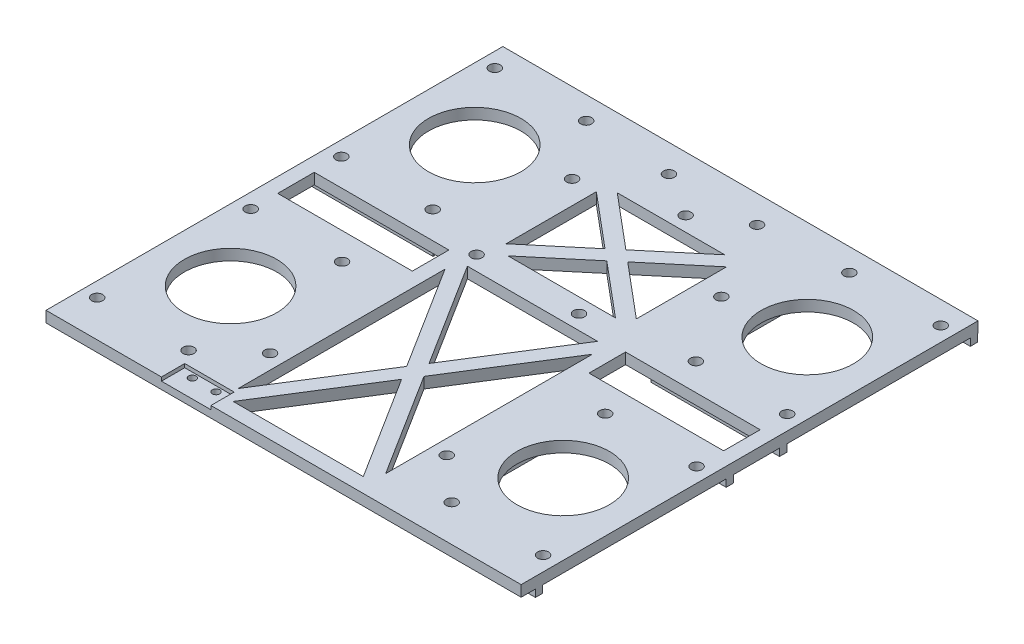
SolidWorks part; units mm, degrees
ref_plane "Front Plane" through (0, 0, 0) normal (0, 0, 1) x (1, 0, 0)
ref_plane "Top Plane" through (0, 0, 0) normal (0, 1, 0) x (1, 0, 0)
ref_plane "Right Plane" through (0, 0, 0) normal (1, 0, 0) x (0, 0, -1)
sketch "Sketch1" plane through (0, 0, 0) normal (0, 1, 0) x (1, 0, 0)
  line L1 (-65, 62.5) -> (65, 62.5)
  line L2 (-65, 62.5) -> (-65, -62.5)
  line L3 (-65, -62.5) -> (65, -62.5)
  line L4 (65, 62.5) -> (65, -62.5)
  line L5 (-65, 62.5) -> (65, -62.5) construction
  line L6 (-65, -62.5) -> (65, 62.5) construction
  point P0 (0, 0)
  dimension "D1" = 130
  dimension "D2" = 125
extrude "Boss-Extrude1" add sketch "Sketch1" along normal blind 5
sketch "Sketch2" plane through (0, 5, 0) normal (0, 1, 0) x (1, 0, 0)
  line L1 (-65, -62.5) -> (65, -62.5) construction
  line L2 (-65, 62.5) -> (-65, -62.5) construction
  circle A0 centre (-61, -52.5) radius 1.5
  circle A1 centre (-36, -52.5) radius 1.5
  circle A2 centre (-36, -10.5) radius 1.5
  circle A3 centre (-61, -10.5) radius 1.5
  circle A4 centre (-45.5, -31.5) radius 12.65
  dimension "D2" = 25.3
  dimension "D7" = 3
  dimension "D8" = 3
  dimension "D9" = 3
  dimension "D10" = 3
  dimension "D1" = 19.5
  dimension "D3" = 31
  dimension "D4" = 4
  dimension "D5" = 10
  dimension "D6" = 10
  dimension "D11" = 4
  dimension "D12" = 42
  dimension "D13" = 42
  dimension "D14" = 25
  dimension "D15" = 25
extrude "Cut-Extrude1" cut sketch "Sketch2" against normal blind 10
ref_plane "Plane1" through (0, 0, 0) normal (-1, 0, 0) x (0, 0, 1)
ref_plane "Plane2" through (0, 0, 0) normal (0, 0, 1) x (1, 0, 0)
mirror "Mirror3" about plane through (0, 0, 0) normal (-1, 0, 0) of "Cut-Extrude1"
sketch "Sketch4" plane through (0, 5, 0) normal (0, 1, 0) x (1, 0, 0)
  line L0 (0, 62.5) -> (0, 47.5) construction
  line L1 (65, 62.5) -> (-65, 62.5) construction
  line L2 (-12.0498, 55) -> (12.0498, 55) construction
  circle A0 centre (0, 47.5) radius 1.5
  circle A1 centre (12.0498, 55) radius 1.5
  circle A2 centre (-12.0498, 55) radius 1.5
  point P9 (0, 55)
  dimension "D2" = 3
  dimension "D3" = 3
  dimension "D4" = 3
  dimension "D1" = 15
  dimension "D5" = 24.0996
extrude "Cut-Extrude3" cut sketch "Sketch4" against normal blind 10
sketch "Sketch5" plane through (0, 0, 0) normal (0, -1, 0) x (1, 0, 0)
  line L0 (-58.15, 31.5) -> (-65, 31.5) construction
  line L1 (-65, -62.5) -> (-65, 62.5) construction
  line L2 (-65, 56.6) -> (-65, 6.4)
  line L3 (-65, 56.6) -> (-31.8, 56.6)
  line L4 (-31.8, 56.6) -> (-31.8, 6.4)
  line L5 (-31.8, 6.4) -> (-65, 6.4)
  line L6 (-65, 58.6) -> (-29.8, 58.6)
  line L7 (-29.8, 58.6) -> (-29.8, 4.4)
  line L8 (-29.8, 4.4) -> (-65, 4.4)
  line L9 (-65, 4.4) -> (-65, 6.4)
  line L10 (-65, 58.6) -> (-65, 56.6)
  circle A0 centre (-45.5, 31.5) radius 12.65 construction
  point P10 (-65, 31.5)
  line M39 (-65, 62.5) -> (-65, -62.5)
  dimension "D1" = 50.2
  dimension "D2" = 33.2
  dimension "D3" = 2
  dimension "D4" = 2
  dimension "D5" = 2
extrude "Boss-Extrude2" add sketch "Sketch5" along normal blind 2 contours L8 L7 L6 L3 L4 L5 M39
mirror "Mirror5" about plane through (0, 0, 0) normal (-1, 0, 0) of "Boss-Extrude2"
ref_plane "Plane3" through (0, 0, 0) normal (0, 0, 1) x (1, 0, 0)
ref_plane "Plane4" through (0, 0, -1.9) normal (0, 0, 1) x (1, 0, 0)
mirror "Mirror7" about plane through (0, 0, -1.9) normal (0, 0, 1) of "Mirror5", "Boss-Extrude2", "Mirror3", "Cut-Extrude1"
ref_plane "Plane5" through (0, 0, 0) normal (0, -1, 0) x (-1, 0, 0)
sketch "Sketch10" plane through (0, 0, 0) normal (0, -1, 0) x (-1, 0, 0)
  circle A0 centre (-24.17, -42.03) radius 1.5
  circle A1 centre (24.17, -42.03) radius 1.5
  circle A2 centre (-8.73, 9.6) radius 1.5
  circle A3 centre (19.29, 9.6) radius 1.5
  circle A4 centre (-24.17, 33.11) radius 1.5
  circle A5 centre (24.17, 40.6) radius 1.5
  dimension "D1" = 3
  dimension "D6" = 3
  dimension "D7" = 3
  dimension "D10" = 3
  dimension "D11" = 3
  dimension "D12" = 3
extrude "Cut-Extrude8" cut sketch "Sketch10" against normal through all
sketch "Sketch11" plane through (0, 0, 0) normal (0, -1, 0) x (1, 0, 0)
  circle A0 centre (-12.0498, -55) radius 2.65
  circle A1 centre (0, -47.5) radius 2.65
  circle A2 centre (12.0498, -55) radius 2.65
  circle A3 centre (-24.17, -40.6) radius 2.65
  circle A4 centre (24.17, -33.11) radius 2.65
  circle A5 centre (8.73, -9.6) radius 2.65
  circle A6 centre (-19.29, -9.6) radius 2.65
  circle A7 centre (-24.17, 42.03) radius 2.65
  circle A8 centre (24.17, 42.03) radius 2.65
  circle A9 centre (-61, -14.3) radius 2.65
  circle A10 centre (-36, -14.3) radius 2.65
  circle A11 centre (-61, -56.3) radius 2.65
  circle A12 centre (-36, -56.3) radius 2.65
  circle A13 centre (36, -56.3) radius 2.65
  circle A14 centre (61, -56.3) radius 2.65
  circle A15 centre (36, -14.3) radius 2.65
  circle A16 centre (61, -14.3) radius 2.65
  circle A17 centre (36, 10.5) radius 2.65
  circle A18 centre (61, 10.5) radius 2.65
  circle A19 centre (61, 52.5) radius 2.65
  circle A20 centre (36, 52.5) radius 2.65
  circle A21 centre (-36, 52.5) radius 2.65
  circle A22 centre (-36, 10.5) radius 2.65
  circle A23 centre (-61, 10.5) radius 2.65
  circle A24 centre (-61, 52.5) radius 2.65
  dimension "D1" = 5.3
  dimension "D2" = 5.3
  dimension "D3" = 5.3
  dimension "D4" = 5.3
  dimension "D5" = 5.3
  dimension "D6" = 5.3
  dimension "D7" = 5.3
  dimension "D8" = 5.3
  dimension "D9" = 5.3
  dimension "D10" = 5.3
  dimension "D11" = 5.3
  dimension "D12" = 5.3
  dimension "D13" = 5.3
  dimension "D14" = 5.3
  dimension "D15" = 5.3
  dimension "D16" = 5.3
  dimension "D17" = 5.3
  dimension "D18" = 5.3
  dimension "D19" = 5.3
  dimension "D20" = 5.3
  dimension "D21" = 5.3
  dimension "D22" = 5.3
  dimension "D23" = 5.3
  dimension "D24" = 5.3
  dimension "D25" = 5.3
extrude "Cut-Extrude9" cut sketch "Sketch11" against normal blind 0.5
sketch "Sketch12" plane through (0, 5, 0) normal (0, 1, 0) x (1, 0, 0)
  line L0 (-65, -62.5) -> (65, -62.5) construction
  line L1 (-20.17, 5.6) -> (20.17, 5.6)
  line L2 (-20.17, 5.6) -> (-20.17, -58.5)
  line L3 (-20.17, -58.5) -> (20.17, -58.5)
  line L4 (20.17, 5.6) -> (20.17, -58.5)
  line L5 (-20.17, 5.6) -> (20.17, -58.5) construction
  line L6 (-20.17, -58.5) -> (20.17, 5.6) construction
  line L7 (-17.8069, 5.6) -> (0, -22.6951)
  line L8 (20.17, -54.7451) -> (2.3631, -26.45)
  line L9 (2.3631, -26.45) -> (20.17, 1.8451)
  line L10 (0, -22.6951) -> (17.8069, 5.6)
  line L11 (-20.17, 1.8451) -> (-2.3631, -26.45)
  line L12 (-2.3631, -26.45) -> (-20.17, -54.7451)
  line L13 (-17.8069, -58.5) -> (0, -30.2049)
  line L14 (0, -30.2049) -> (17.8069, -58.5)
  circle A0 centre (-19.29, 9.6) radius 1.5 construction
  circle A1 centre (-24.17, -42.03) radius 1.5 construction
  circle A2 centre (24.17, -42.03) radius 1.5 construction
  dimension "D2" = 4
  dimension "D3" = 4
  dimension "D1" = 4
  dimension "D4" = 4
  dimension "D5" = 2
  dimension "D6" = 2
  dimension "D7" = 2
  dimension "D8" = 2
extrude "Cut-Extrude10" cut sketch "Sketch12" against normal through all contours L12 L11 L2 | L7 L10 L1 | L9 L8 L4 | L14 L13 L3
sketch "Sketch13" plane through (0, 5, 0) normal (0, 1, 0) x (1, 0, 0)
  line L0 (-61, 14.3) -> (-61, -10.5) construction
  line L1 (-61, 1.9) -> (-61, -3.1)
  line L2 (-61, -3.1) -> (-24.17, -3.1)
  line L3 (-24.17, -3.1) -> (-24.17, 6.9)
  line L4 (-24.17, 6.9) -> (-61, 6.9)
  line L5 (-61, 6.9) -> (-61, 1.9)
  line L6 (-20.17, 1.8451) -> (-20.17, -54.7451) construction
  dimension "D1" = 10
  dimension "D2" = 5
  dimension "D3" = 4
extrude "Cut-Extrude11" cut sketch "Sketch13" against normal through all
mirror "Mirror9" about plane through (0, 0, 0) normal (-1, 0, 0) of "Cut-Extrude11"
sketch "Sketch14" plane through (0, 5, 0) normal (0, 1, 0) x (1, 0, 0)
  line L0 (-17.8069, 43.5) -> (17.8069, 13.6) construction
  line L1 (-17.8069, 43.5) -> (17.8069, 43.5)
  line L2 (-17.8069, 43.5) -> (-17.8069, 13.6)
  line L3 (-17.8069, 13.6) -> (17.8069, 13.6)
  line L4 (17.8069, 43.5) -> (17.8069, 13.6)
  line L5 (-17.8069, 13.6) -> (17.8069, 43.5) construction
  line L6 (-17.8069, 40.8886) -> (-3.1104, 28.55)
  line L7 (-3.1104, 28.55) -> (-17.8069, 16.2114)
  line L8 (-14.6965, 13.6) -> (0, 25.9386)
  line L9 (0, 25.9386) -> (14.6965, 13.6)
  line L10 (17.8069, 16.2114) -> (3.1104, 28.55)
  line L11 (3.1104, 28.55) -> (17.8069, 40.8886)
  line L12 (14.6965, 43.5) -> (0, 31.1614)
  line L13 (0, 31.1614) -> (-14.6965, 43.5)
  circle A0 centre (0, 47.5) radius 1.5 construction
  circle A1 centre (8.73, 9.6) radius 1.5 construction
  dimension "D1" = 4
  dimension "D2" = 4
  dimension "D3" = 2
  dimension "D4" = 2
  dimension "D5" = 2
  dimension "D6" = 2
  dimension "D7" = 2
  dimension "D8" = 2
  dimension "D9" = 2
  dimension "D10" = 2
extrude "Cut-Extrude12" cut sketch "Sketch14" against normal through all contours L7 L6 L2 | L13 L12 L1 | L11 L10 L4 | L9 L8 L3
sketch "Sketch15" plane through (0, 5, 0) normal (0, 1, 0) x (1, 0, 0)
  line L1 (-63.5, 58.8) -> (-58.5, 58.8)
  line L2 (-63.5, 58.8) -> (-63.5, 53.8)
  line L3 (-63.5, 53.8) -> (-58.5, 53.8)
  line L4 (65, -62.5) -> (65, 62.5)
  line L5 (65, 62.5) -> (-65, 62.5)
  line L6 (-65, 62.5) -> (-65, -62.5)
  line L7 (-65, -62.5) -> (65, -62.5)
  line L8 (65, -62.5) -> (65, 62.5)
  line L9 (65, 62.5) -> (-65, 62.5)
  line L10 (-65, 62.5) -> (-65, -62.5)
  line L11 (-65, -62.5) -> (65, -62.5)
  line L12 (-58.5, 58.8) -> (-58.5, 53.8)
  line L13 (-63.5, 58.8) -> (-58.5, 53.8) construction
  line L14 (-63.5, 53.8) -> (-58.5, 58.8) construction
  line L15 (-38.5, 58.8) -> (-33.5, 58.8)
  line L16 (-38.5, 58.8) -> (-38.5, 53.8)
  line L17 (-38.5, 53.8) -> (-33.5, 53.8)
  line L18 (-33.5, 58.8) -> (-33.5, 53.8)
  line L19 (-38.5, 58.8) -> (-33.5, 53.8) construction
  line L20 (-38.5, 53.8) -> (-33.5, 58.8) construction
  line L21 (-14.5498, 57.5) -> (-9.5498, 57.5)
  line L22 (-14.5498, 57.5) -> (-14.5498, 52.5)
  line L23 (-14.5498, 52.5) -> (-9.5498, 52.5)
  line L24 (-9.5498, 57.5) -> (-9.5498, 52.5)
  line L25 (-14.5498, 57.5) -> (-9.5498, 52.5) construction
  line L26 (-14.5498, 52.5) -> (-9.5498, 57.5) construction
  line L27 (-2.5, 50) -> (2.5, 50)
  line L28 (-2.5, 50) -> (-2.5, 45)
  line L29 (-2.5, 45) -> (2.5, 45)
  line L30 (2.5, 50) -> (2.5, 45)
  line L31 (-2.5, 50) -> (2.5, 45) construction
  line L32 (-2.5, 45) -> (2.5, 50) construction
  line L33 (9.5498, 57.5) -> (14.5498, 57.5)
  line L34 (9.5498, 57.5) -> (9.5498, 52.5)
  line L35 (9.5498, 52.5) -> (14.5498, 52.5)
  line L36 (14.5498, 57.5) -> (14.5498, 52.5)
  line L37 (9.5498, 57.5) -> (14.5498, 52.5) construction
  line L38 (9.5498, 52.5) -> (14.5498, 57.5) construction
  line L39 (33.5, 58.8) -> (38.5, 58.8)
  line L40 (33.5, 58.8) -> (33.5, 53.8)
  line L41 (33.5, 53.8) -> (38.5, 53.8)
  line L42 (38.5, 58.8) -> (38.5, 53.8)
  line L43 (33.5, 58.8) -> (38.5, 53.8) construction
  line L44 (33.5, 53.8) -> (38.5, 58.8) construction
  line L45 (63.5, 58.8) -> (58.5, 58.8)
  line L46 (63.5, 58.8) -> (63.5, 53.8)
  line L47 (63.5, 53.8) -> (58.5, 53.8)
  line L48 (58.5, 58.8) -> (58.5, 53.8)
  line L49 (63.5, 58.8) -> (58.5, 53.8) construction
  line L50 (63.5, 53.8) -> (58.5, 58.8) construction
  line L51 (33.5, 16.8) -> (38.5, 16.8)
  line L52 (33.5, 16.8) -> (33.5, 11.8)
  line L53 (33.5, 11.8) -> (38.5, 11.8)
  line L54 (38.5, 16.8) -> (38.5, 11.8)
  line L55 (33.5, 16.8) -> (38.5, 11.8) construction
  line L56 (33.5, 11.8) -> (38.5, 16.8) construction
  line L57 (63.5, 16.8) -> (58.5, 16.8)
  line L58 (63.5, 16.8) -> (63.5, 11.8)
  line L59 (63.5, 11.8) -> (58.5, 11.8)
  line L60 (58.5, 16.8) -> (58.5, 11.8)
  line L61 (63.5, 16.8) -> (58.5, 11.8) construction
  line L62 (63.5, 11.8) -> (58.5, 16.8) construction
  line L63 (21.67, 35.61) -> (26.67, 35.61)
  line L64 (21.67, 35.61) -> (21.67, 30.61)
  line L65 (21.67, 30.61) -> (26.67, 30.61)
  line L66 (26.67, 35.61) -> (26.67, 30.61)
  line L67 (21.67, 35.61) -> (26.67, 30.61) construction
  line L68 (21.67, 30.61) -> (26.67, 35.61) construction
  line L69 (33.5, -8) -> (38.5, -8)
  line L70 (33.5, -8) -> (33.5, -13)
  line L71 (33.5, -13) -> (38.5, -13)
  line L72 (38.5, -8) -> (38.5, -13)
  line L73 (33.5, -8) -> (38.5, -13) construction
  line L74 (33.5, -13) -> (38.5, -8) construction
  line L75 (63.5, -8) -> (58.5, -8)
  line L76 (63.5, -8) -> (63.5, -13)
  line L77 (63.5, -13) -> (58.5, -13)
  line L78 (58.5, -8) -> (58.5, -13)
  line L79 (63.5, -8) -> (58.5, -13) construction
  line L80 (63.5, -13) -> (58.5, -8) construction
  line L81 (21.67, -39.53) -> (26.67, -39.53)
  line L82 (21.67, -39.53) -> (21.67, -44.53)
  line L83 (21.67, -44.53) -> (26.67, -44.53)
  line L84 (26.67, -39.53) -> (26.67, -44.53)
  line L85 (21.67, -39.53) -> (26.67, -44.53) construction
  line L86 (21.67, -44.53) -> (26.67, -39.53) construction
  line L87 (38.5, -50) -> (33.5, -50)
  line L88 (38.5, -50) -> (38.5, -55)
  line L89 (38.5, -55) -> (33.5, -55)
  line L90 (33.5, -50) -> (33.5, -55)
  line L91 (38.5, -50) -> (33.5, -55) construction
  line L92 (38.5, -55) -> (33.5, -50) construction
  line L93 (63.5, -50) -> (58.5, -50)
  line L94 (63.5, -50) -> (63.5, -55)
  line L95 (63.5, -55) -> (58.5, -55)
  line L96 (58.5, -50) -> (58.5, -55)
  line L97 (63.5, -50) -> (58.5, -55) construction
  line L98 (63.5, -55) -> (58.5, -50) construction
  line L99 (-26.67, -39.53) -> (-21.67, -39.53)
  line L100 (-26.67, -39.53) -> (-26.67, -44.53)
  line L101 (-26.67, -44.53) -> (-21.67, -44.53)
  line L102 (-21.67, -39.53) -> (-21.67, -44.53)
  line L103 (-26.67, -39.53) -> (-21.67, -44.53) construction
  line L104 (-26.67, -44.53) -> (-21.67, -39.53) construction
  line L105 (-38.5, -50) -> (-33.5, -50)
  line L106 (-38.5, -50) -> (-38.5, -55)
  line L107 (-38.5, -55) -> (-33.5, -55)
  line L108 (-33.5, -50) -> (-33.5, -55)
  line L109 (-38.5, -50) -> (-33.5, -55) construction
  line L110 (-38.5, -55) -> (-33.5, -50) construction
  line L111 (-38.5, -8) -> (-33.5, -8)
  line L112 (-38.5, -8) -> (-38.5, -13)
  line L113 (-38.5, -13) -> (-33.5, -13)
  line L114 (-33.5, -8) -> (-33.5, -13)
  line L115 (-38.5, -8) -> (-33.5, -13) construction
  line L116 (-38.5, -13) -> (-33.5, -8) construction
  line L117 (6.23, 12.1) -> (11.23, 12.1)
  line L118 (6.23, 12.1) -> (6.23, 7.1)
  line L119 (6.23, 7.1) -> (11.23, 7.1)
  line L120 (11.23, 12.1) -> (11.23, 7.1)
  line L121 (6.23, 12.1) -> (11.23, 7.1) construction
  line L122 (6.23, 7.1) -> (11.23, 12.1) construction
  line L123 (-21.79, 12.1) -> (-16.79, 12.1)
  line L124 (-21.79, 12.1) -> (-21.79, 7.1)
  line L125 (-21.79, 7.1) -> (-16.79, 7.1)
  line L126 (-16.79, 12.1) -> (-16.79, 7.1)
  line L127 (-21.79, 12.1) -> (-16.79, 7.1) construction
  line L128 (-21.79, 7.1) -> (-16.79, 12.1) construction
  line L129 (-26.67, 43.1) -> (-21.67, 43.1)
  line L130 (-26.67, 43.1) -> (-26.67, 38.1)
  line L131 (-26.67, 38.1) -> (-21.67, 38.1)
  line L132 (-21.67, 43.1) -> (-21.67, 38.1)
  line L133 (-26.67, 43.1) -> (-21.67, 38.1) construction
  line L134 (-26.67, 38.1) -> (-21.67, 43.1) construction
  line L135 (-63.5, 16.8) -> (-58.5, 16.8)
  line L136 (-63.5, 16.8) -> (-63.5, 11.8)
  line L137 (-63.5, 11.8) -> (-58.5, 11.8)
  line L138 (-58.5, 16.8) -> (-58.5, 11.8)
  line L139 (-63.5, 16.8) -> (-58.5, 11.8) construction
  line L140 (-63.5, 11.8) -> (-58.5, 16.8) construction
  line L141 (-38.5, 16.8) -> (-33.5, 16.8)
  line L142 (-38.5, 16.8) -> (-38.5, 11.8)
  line L143 (-38.5, 11.8) -> (-33.5, 11.8)
  line L144 (-33.5, 16.8) -> (-33.5, 11.8)
  line L145 (-38.5, 16.8) -> (-33.5, 11.8) construction
  line L146 (-38.5, 11.8) -> (-33.5, 16.8) construction
  line L147 (-63.5, -8) -> (-58.5, -8)
  line L148 (-63.5, -8) -> (-63.5, -13)
  line L149 (-63.5, -13) -> (-58.5, -13)
  line L150 (-58.5, -8) -> (-58.5, -13)
  line L151 (-63.5, -8) -> (-58.5, -13) construction
  line L152 (-63.5, -13) -> (-58.5, -8) construction
  line L153 (-63.5, -50) -> (-58.5, -50)
  line L154 (-63.5, -50) -> (-63.5, -55)
  line L155 (-63.5, -55) -> (-58.5, -55)
  line L156 (-58.5, -50) -> (-58.5, -55)
  line L157 (-63.5, -50) -> (-58.5, -55) construction
  line L158 (-63.5, -55) -> (-58.5, -50) construction
  circle A0 centre (-61, 56.3) radius 1.5 construction
  circle A1 centre (-36, 56.3) radius 1.5 construction
  circle A2 centre (-12.0498, 55) radius 1.5 construction
  circle A3 centre (0, 47.5) radius 1.5 construction
  circle A4 centre (12.0498, 55) radius 1.5 construction
  circle A5 centre (36, 56.3) radius 1.5 construction
  circle A6 centre (61, 56.3) radius 1.5 construction
  circle A7 centre (24.17, 33.11) radius 1.5 construction
  circle A8 centre (36, 14.3) radius 1.5 construction
  circle A9 centre (61, 14.3) radius 1.5 construction
  circle A10 centre (-24.17, 40.6) radius 1.5 construction
  circle A11 centre (-61, 14.3) radius 1.5 construction
  circle A12 centre (-36, 14.3) radius 1.5 construction
  circle A13 centre (-19.29, 9.6) radius 1.5 construction
  circle A14 centre (8.73, 9.6) radius 1.5 construction
  circle A15 centre (-61, -10.5) radius 1.5 construction
  circle A16 centre (-36, -10.5) radius 1.5 construction
  circle A17 centre (36, -10.5) radius 1.5 construction
  circle A18 centre (61, -10.5) radius 1.5 construction
  circle A19 centre (61, -52.5) radius 1.5 construction
  circle A20 centre (36, -52.5) radius 1.5 construction
  circle A21 centre (24.17, -42.03) radius 1.5 construction
  circle A22 centre (-24.17, -42.03) radius 1.5 construction
  circle A23 centre (-36, -52.5) radius 1.5 construction
  circle A24 centre (-61, -52.5) radius 1.5 construction
  point P2 (-61, 56.3)
  point P12 (-36, 56.3)
  point P20 (-12.0498, 55)
  point P26 (0, 47.5)
  point P32 (12.0498, 55)
  point P38 (36, 56.3)
  point P44 (61, 56.3)
  point P50 (36, 14.3)
  point P56 (61, 14.3)
  point P62 (24.17, 33.11)
  point P84 (36, -10.5)
  point P90 (61, -10.5)
  point P96 (24.17, -42.03)
  point P102 (36, -52.5)
  point P108 (61, -52.5)
  point P114 (-24.17, -42.03)
  point P120 (-36, -52.5)
  point P126 (-36, -10.5)
  point P132 (8.73, 9.6)
  point P138 (-19.29, 9.6)
  point P144 (-24.17, 40.6)
  point P150 (-61, 14.3)
  point P156 (-36, 14.3)
  point P162 (-61, -10.5)
  point P168 (-61, -52.5)
  dimension "D2" = 2.5
  dimension "D3" = 2.5
  dimension "D4" = 2.5
  dimension "D5" = 2.5
  dimension "D6" = 2.5
  dimension "D7" = 2.5
  dimension "D8" = 2.5
  dimension "D9" = 2.5
  dimension "D10" = 2.5
  dimension "D11" = 2.5
  dimension "D12" = 2.5
  dimension "D13" = 2.5
  dimension "D15" = 2.5
  dimension "D16" = 2.5
  dimension "D17" = 2.5
  dimension "D18" = 2.5
  dimension "D19" = 2.5
  dimension "D20" = 2.5
  dimension "D21" = 2.5
  dimension "D22" = 2.5
  dimension "D23" = 2.5
  dimension "D24" = 2.5
  dimension "D25" = 2.5
  dimension "D26" = 2.5
  dimension "D27" = 2.5
  dimension "D28" = 2.5
  dimension "D29" = 2.5
  dimension "D30" = 2.5
  dimension "D31" = 2.5
  dimension "D32" = 2.5
  dimension "D33" = 2.5
  dimension "D34" = 2.5
  dimension "D35" = 2.5
  dimension "D36" = 2.5
  dimension "D37" = 2.5
  dimension "D38" = 2.5
  dimension "D39" = 2.5
  dimension "D40" = 2.5
  dimension "D41" = 2.5
  dimension "D42" = 2.5
  dimension "D43" = 2.5
  dimension "D44" = 2.5
  dimension "D45" = 2.5
  dimension "D46" = 2.5
  dimension "D47" = 2.5
  dimension "D48" = 2.5
  dimension "D49" = 2.5
  dimension "D14" = 2.5
  dimension "D1" = 0
extrude "Cut-Extrude14" cut sketch "Sketch15" against normal blind 2
ref_plane "Plane6" through (0, 13, 0) normal (0, 1, 0) x (1, 0, 0)
sketch "Sketch17" plane through (0, 13, 0) normal (0, 1, 0) x (1, 0, 0)
  line L1 (-68.0587, 64.2777) -> (69.5711, 64.2777)
  line L2 (-68.0587, 64.2777) -> (-68.0587, -66.7984)
  line L3 (-68.0587, -66.7984) -> (69.5711, -66.7984)
  line L4 (69.5711, 64.2777) -> (69.5711, -66.7984)
extrude "Cut-Extrude15" cut sketch "Sketch17" against normal blind 2 from surface at -8 starting at face at (-61, 5, -15.8)
sketch "Sketch18" plane through (0, 3, 0) normal (0, 1, 0) x (1, 0, 0)
  line L0 (-65, -62.5) -> (65, -62.5) construction
  line L1 (-33.412, -56.1297) -> (-19.8846, -56.1297)
  line L2 (-33.412, -56.1297) -> (-33.412, -62.5)
  line L3 (-33.412, -62.5) -> (-19.8846, -62.5)
  line L4 (-19.8846, -56.1297) -> (-19.8846, -62.5)
extrude "Cut-Extrude16" cut sketch "Sketch18" against normal blind 1
sketch "Sketch19" plane through (0, 2, 0) normal (0, 1, 0) x (1, 0, 0)
  circle A0 centre (-23.4201, -57.55) radius 1
  circle A1 centre (-29.9201, -57.55) radius 1
extrude "Cut-Extrude17" cut sketch "Sketch19" against normal blind 5
sketch "Sketch20" plane through (0, 0, 0) normal (0, -1, 0) x (1, 0, 0)
  line L1 (-32.8112, 59.7055) -> (-26.1535, 59.7055)
  line L2 (-32.8112, 59.7055) -> (-32.8112, 55.2822)
  line L3 (-32.8112, 55.2822) -> (-26.1535, 55.2822)
  line L4 (-26.1535, 59.7055) -> (-26.1535, 55.2822)
extrude "Cut-Extrude18" cut sketch "Sketch20" along normal up to surface (2 mm away) up to face at (-44.392, -2, 36.71)
